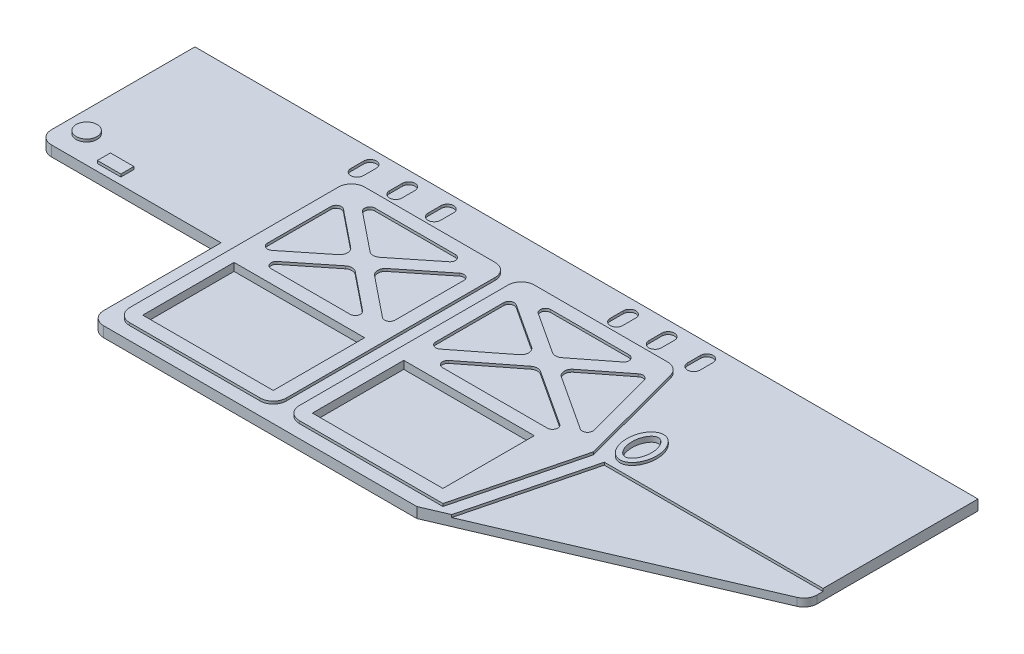
SolidWorks part; units mm, degrees
ref_plane "Front Plane" through (0, 0, 0) normal (0, 0, 1) x (1, 0, 0)
ref_plane "Top Plane" through (0, 0, 0) normal (0, 1, 0) x (1, 0, 0)
ref_plane "Right Plane" through (0, 0, 0) normal (1, 0, 0) x (0, 0, -1)
sketch "Sketch1" plane through (0, 0, 0) normal (0, 0, 1) x (1, 0, 0)
  line L0 (0, 0) -> (0, 254) construction
  line L1 (-381, 0) -> (0, 0)
  line L3 (-381, 6.35) -> (0, 6.35)
  line L4 (0, 0) -> (0, 6.35)
  line L5 (-381, 0) -> (-381, 6.35)
extrude "Boss-Extrude1" add sketch "Sketch1" along normal blind 139.7
sketch "Sketch2" plane through (0, 0, 0) normal (0, -1, 0) x (1, 0, 0)
  line L1 (-406.4, 139.7) -> (-406.4, 0) construction
  line L2 (-374.65, 76.2) -> (-292.1, 76.2)
  line L3 (-292.1, 76.2) -> (-292.1, 133.35)
  line L4 (-381, 139.7) -> (0, 139.7) construction
  line L5 (-285.75, 139.7) -> (-133.35, 139.7)
  line L6 (-133.35, 139.7) -> (-3.8486, 84.1994)
  line L7 (0, 139.7) -> (0, 0) construction
  line L8 (0, 78.3628) -> (0, 0)
  line L9 (0, 0) -> (-381, 0)
  line L10 (-381, 69.85) -> (-381, 0)
  line L11 (-381, 139.7) -> (-381, 0) construction
  arc A0 (-3.8486, 84.1994) -> (0, 78.3628) centre (-6.35, 78.3628) cw
  arc A1 (-292.1, 133.35) -> (-285.75, 139.7) centre (-285.75, 133.35) cw
  arc A3 (-381, 69.85) -> (-374.65, 76.2) centre (-374.65, 69.85) cw
  point P17 (0, 82.55)
  point P20 (-292.1, 139.7)
  point P21 (-381, 76.2)
  point P23 (-406.4, 76.2)
  dimension "D5" = 6.35
  dimension "D1" = 6.35
  dimension "D2" = 114.3
  dimension "D3" = 158.75
  dimension "D4" = 82.55
extrude "Cut-Extrude1" cut sketch "Sketch2" against normal through all
sketch "Sketch3" plane through (0, 6.35, 0) normal (0, 1, 0) x (1, 0, 0)
  line L0 (-133.35, -139.7) -> (-285.75, -139.7) construction
  line L1 (-279.4, -127) -> (-215.9, -127)
  line L2 (-279.4, -127) -> (-279.4, -82.55)
  line L3 (-279.4, -82.55) -> (-215.9, -82.55)
  line L4 (-215.9, -127) -> (-215.9, -82.55)
  line L5 (-196.85, -127) -> (-133.35, -127)
  line L6 (-196.85, -127) -> (-196.85, -82.55)
  line L7 (-196.85, -82.55) -> (-133.35, -82.55)
  line L8 (-133.35, -127) -> (-133.35, -82.55)
  line L9 (-292.1, -76.2) -> (-292.1, -133.35) construction
  dimension "D1" = 44.45
  dimension "D2" = 12.7
  dimension "D3" = 12.7
  dimension "D4" = 63.5
  dimension "D5" = 19.05
  dimension "D6" = 44.45
  dimension "D7" = 12.7
  dimension "D8" = 63.5
extrude "Cut-Extrude2" cut sketch "Sketch3" against normal through all contours L5 L8 L7 L6 | L1 L4 L3 L2
sketch "Sketch4" plane through (0, 0, 0) normal (0, -1, 0) x (1, 0, 0)
  line L0 (-285.75, 139.7) -> (-133.35, 139.7) construction
  line L1 (-279.4, 133.35) -> (-215.9, 133.35)
  line L2 (-285.75, 127) -> (-285.75, 25.4)
  line L3 (-279.4, 19.05) -> (-215.9, 19.05)
  line L4 (-209.55, 127) -> (-209.55, 25.4)
  line L5 (-127, 133.35) -> (-196.85, 133.35)
  line L7 (-131.8807, 19.05) -> (-196.85, 19.05)
  line L8 (-203.2, 127) -> (-203.2, 25.4)
  line L9 (-292.1, 76.2) -> (-292.1, 133.35) construction
  line L11 (-381, 0) -> (0, 0) construction
  line L12 (-215.9, 127) -> (-215.9, 82.55) construction
  line L13 (-127, 133.35) -> (-112.1376, 74.8789)
  line L14 (-112.1376, 74.8789) -> (-125.7444, 23.7664)
  arc A0 (-196.85, 133.35) -> (-203.2, 127) centre (-196.85, 127) ccw
  arc A1 (-215.9, 133.35) -> (-209.55, 127) centre (-215.9, 127) cw
  arc A2 (-279.4, 133.35) -> (-285.75, 127) centre (-279.4, 127) ccw
  arc A3 (-285.75, 25.4) -> (-279.4, 19.05) centre (-279.4, 25.4) ccw
  arc A4 (-215.9, 19.05) -> (-209.55, 25.4) centre (-215.9, 25.4) ccw
  arc A5 (-196.85, 19.05) -> (-203.2, 25.4) centre (-196.85, 25.4) cw
  arc A6 (-131.8807, 19.05) -> (-125.7444, 23.7664) centre (-131.8807, 25.4) ccw
  dimension "D3" = 6.35
  dimension "D1" = 6.35
  dimension "D2" = 6.35
  dimension "D4" = 6.35
  dimension "D5" = 19.05
  dimension "D6" = 6.35
  dimension "D7" = 6.35
  dimension "D8" = 19.05
extrude "Cut-Extrude3" cut sketch "Sketch4" against normal blind 1.27
sketch "Sketch5" plane through (0, 0, 0) normal (0, -1, 0) x (1, 0, 0)
  line L0 (-250.8616, 56.914) -> (-269.3149, 71.6766)
  line L1 (-248.4216, 50.9666) -> (-248.4331, 50.9773) construction
  line L3 (-267.7282, 76.2) -> (-229.317, 76.2)
  line L4 (-257.258, 53.8991) -> (-275.2733, 68.3113)
  line L5 (-184.3234, 76.2) -> (-133.6398, 76.2)
  line L6 (-196.85, 82.55) -> (-133.35, 82.55) construction
  line L9 (-142.8427, 29.9409) -> (-159.4602, 42.9343)
  line L10 (-227.2884, 29.9234) -> (-246.082, 44.9583)
  line L12 (-131.9836, 71.533) -> (-158.9921, 53.9033)
  line L15 (-124.9851, 68.5182) -> (-151.5288, 51.1918)
  line L21 (-220.0267, 32.246) -> (-239.6856, 47.9731)
  line L24 (-275.269, 33.4756) -> (-257.2515, 47.954)
  line L26 (-131.8807, 25.4) -> (-118.6989, 74.9159)
  line L28 (-131.8807, 25.4) -> (-118.6989, 74.9159)
  line L30 (-118.6989, 74.9159) -> (-131.9379, 127)
  line L37 (-269.5564, 29.9199) -> (-250.8486, 44.9531)
  line L38 (-215.9, 34.2294) -> (-215.9, 67.7374)
  line L40 (-248.5328, 50.9091) -> (-248.3486, 51.0351) construction
  line L41 (-246.095, 56.9191) -> (-227.7259, 71.6801)
  line L42 (-248.5328, 50.9091) -> (-248.5037, 50.8894) construction
  line L43 (-228.8751, 25.4) -> (-267.9653, 25.4)
  line L44 (-248.3486, 51.0351) -> (-248.5037, 50.8894) construction
  line L45 (-279.4, 66.3279) -> (-279.4, 35.4556)
  line L46 (-239.6921, 53.9182) -> (-220.031, 69.7173)
  line L47 (-133.6398, 76.2) -> (-133.372, 76.2)
  line L51 (-134.0223, 31.1049) -> (-151.793, 45)
  line L55 (-163.4215, 54.0923) -> (-185.888, 71.6591)
  line L57 (-164.1074, 50.5642) -> (-164.3654, 50.8) construction
  line L58 (-131.9379, 127) -> (-196.85, 127)
  line L59 (-171.3529, 45.8348) -> (-192.9216, 31.7558)
  line L60 (-164.3654, 50.8) -> (-164.0586, 50.5961) construction
  line L61 (-196.85, 127) -> (-196.85, 25.4)
  line L62 (-164.0586, 50.5961) -> (-164.1074, 50.5642)
  line L63 (-171.0886, 52.0266) -> (-192.7454, 68.9603)
  line L65 (-163.8896, 43.1233) -> (-183.8917, 30.067)
  line L66 (-196.85, 127) -> (-196.85, 25.4)
  line L68 (-196.85, 25.4) -> (-131.8807, 25.4)
  line L70 (-196.85, 25.4) -> (-131.8807, 25.4)
  arc A0 (-257.258, 53.8991) -> (-257.2515, 47.954) centre (-259.6381, 50.924) cw
  arc A1 (-250.8486, 44.9531) -> (-246.082, 44.9583) centre (-248.462, 41.9831) cw
  arc A2 (-239.6856, 47.9731) -> (-239.6921, 53.9182) centre (-237.3055, 50.9483) cw
  arc A3 (-250.8616, 56.914) -> (-246.095, 56.9191) centre (-248.4815, 59.8891) ccw
  arc A4 (-267.7282, 76.2) -> (-269.3149, 71.6766) centre (-267.7282, 73.66) ccw
  arc A5 (-275.2733, 68.3113) -> (-279.4, 66.3279) centre (-276.86, 66.3279) ccw
  arc A6 (-279.4, 35.4556) -> (-275.269, 33.4756) centre (-276.86, 35.4556) ccw
  arc A7 (-267.9653, 25.4) -> (-269.5564, 29.9199) centre (-267.9653, 27.94) cw
  arc A8 (-227.2884, 29.9234) -> (-228.8751, 25.4) centre (-228.8751, 27.94) cw
  arc A9 (-220.0267, 32.246) -> (-215.9, 34.2294) centre (-218.44, 34.2294) ccw
  arc A10 (-215.9, 67.7374) -> (-220.031, 69.7173) centre (-218.44, 67.7374) ccw
  arc A11 (-227.7259, 71.6801) -> (-229.317, 76.2) centre (-229.317, 73.66) ccw
  arc A12 (-183.8917, 30.067) -> (-182.5033, 25.4) centre (-182.5033, 27.94) ccw
  arc A13 (-142.8427, 29.9409) -> (-144.4073, 25.4) centre (-144.4073, 27.94) cw
  arc A14 (-124.9851, 68.5182) -> (-121.1422, 65.7378) centre (-123.5967, 66.3912) cw
  arc A15 (-133.372, 76.2) -> (-131.9836, 71.533) centre (-133.372, 73.66) cw
  arc A16 (-134.0223, 31.1049) -> (-130.0033, 32.4524) centre (-132.4578, 33.1058) ccw
  arc A17 (-192.9216, 31.7558) -> (-196.85, 33.8828) centre (-194.31, 33.8828) cw
  arc A18 (-196.85, 66.9593) -> (-192.7454, 68.9603) centre (-194.31, 66.9593) cw
  arc A19 (-185.888, 71.6591) -> (-184.3234, 76.2) centre (-184.3234, 73.66) cw
  arc A20 (-171.3529, 45.8348) -> (-171.0886, 52.0266) centre (-173.4355, 49.0252) ccw
  arc A21 (-163.8896, 43.1233) -> (-159.4602, 42.9343) centre (-161.807, 39.9329) cw
  arc A22 (-151.793, 45) -> (-151.5288, 51.1918) centre (-149.4462, 48.0014) cw
  arc A23 (-158.9921, 53.9033) -> (-163.4215, 54.0923) centre (-161.0746, 57.0937) cw
  point P13 (-247.9043, 50.4821)
  point P14 (-248.3486, 51.0351)
  point P39 (-243.3962, 50.9416)
  point P55 (-157.9377, 50.8)
  point P56 (-164.3654, 50.8)
  point P88 (-166.8929, 48.746)
  dimension "D5" = 3.81
  dimension "D1" = 2.54
  dimension "D4" = 2.54
  dimension "D6" = 2.54
  dimension "D7" = 2.54
  dimension "D8" = 3.81
  dimension "D3" = 6.35
  dimension "D2" = 6.35
extrude "Cut-Extrude4" cut sketch "Sketch5" against normal blind 1.27 contours A23 L12 A15 L47 L5 A19 L55 | A22 L51 A16 L28 A14 L15 | A21 L65 A12 L70 A13 L9 | L59 A20 L63 A18 L66 A17 | L38 A10 L46 A2 L21 A9 | A8 L10 A1 L37 A7 L43 | L41 A11 L3 A4 L0 A3 | L45 A6 L24 A0 L4 A5
sketch "Sketch6" plane through (0, 1.27, 0) normal (0, -1, 0) x (1, 0, 0)
  line L0 (-288.798, 6.985) -> (-288.798, 13.335) construction
  line L1 (-291.846, 6.985) -> (-291.846, 13.335)
  line L2 (-285.75, 6.985) -> (-285.75, 13.335)
  line L3 (-270.002, 6.985) -> (-270.002, 13.335) construction
  line L6 (-273.05, 6.985) -> (-273.05, 13.335)
  line L9 (-266.954, 6.985) -> (-266.954, 13.335)
  line L12 (-251.206, 6.985) -> (-251.206, 13.335) construction
  line L15 (-381, 0) -> (0, 0) construction
  line L17 (-254.254, 6.985) -> (-254.254, 13.335)
  line L18 (-248.158, 6.985) -> (-248.158, 13.335)
  line L19 (-162.56, 6.985) -> (-162.56, 13.335) construction
  line L20 (-165.608, 6.985) -> (-165.608, 13.335)
  line L21 (-159.512, 6.985) -> (-159.512, 13.335)
  line L22 (-143.764, 6.985) -> (-143.764, 13.335) construction
  line L23 (-146.812, 6.985) -> (-146.812, 13.335)
  line L24 (-140.716, 6.985) -> (-140.716, 13.335)
  line L25 (-124.968, 6.985) -> (-124.968, 13.335) construction
  line L26 (-128.016, 6.985) -> (-128.016, 13.335)
  line L27 (-121.92, 6.985) -> (-121.92, 13.335)
  line L28 (-381, 69.85) -> (-381, 0) construction
  arc A0 (-291.846, 6.985) -> (-285.75, 6.985) centre (-288.798, 6.985) ccw
  arc A1 (-285.75, 13.335) -> (-291.846, 13.335) centre (-288.798, 13.335) ccw
  arc A5 (-286.5205, 4.8853) -> (-286.5215, 4.9583) centre (-289.4119, 4.8853) ccw
  arc A7 (-286.5205, 4.8853) -> (-286.5215, 4.9583) centre (-289.4119, 4.8853) ccw
  arc A9 (-286.5205, 4.8853) -> (-286.5215, 4.9583) centre (-289.4119, 4.8853) ccw
  arc A10 (-273.05, 6.985) -> (-266.954, 6.985) centre (-270.002, 6.985) ccw
  arc A11 (-266.954, 13.335) -> (-273.05, 13.335) centre (-270.002, 13.335) ccw
  arc A12 (-254.254, 6.985) -> (-248.158, 6.985) centre (-251.206, 6.985) ccw
  arc A13 (-248.158, 13.335) -> (-254.254, 13.335) centre (-251.206, 13.335) ccw
  arc A14 (-165.608, 6.985) -> (-159.512, 6.985) centre (-162.56, 6.985) ccw
  arc A15 (-159.512, 13.335) -> (-165.608, 13.335) centre (-162.56, 13.335) ccw
  arc A16 (-146.812, 6.985) -> (-140.716, 6.985) centre (-143.764, 6.985) ccw
  arc A17 (-140.716, 13.335) -> (-146.812, 13.335) centre (-143.764, 13.335) ccw
  arc A18 (-128.016, 6.985) -> (-121.92, 6.985) centre (-124.968, 6.985) ccw
  arc A19 (-121.92, 13.335) -> (-128.016, 13.335) centre (-124.968, 13.335) ccw
  point P2 (-288.798, 10.16)
  point P9 (-289.4119, -1.7103)
  point P11 (-270.002, 10.16)
  point P16 (-289.4119, 0)
  point P18 (-251.206, 10.16)
  point P23 (-289.4119, 0)
  point P28 (-162.56, 10.16)
  point P30 (-289.4119, 0)
  point P41 (-143.764, 10.16)
  point P48 (-124.968, 10.16)
  point P57 (-248.158, 10.16)
  dimension "D1" = 3.048
  dimension "D2" = 6.35
  dimension "D3" = 10.16
  dimension "D4" = 95.25
  dimension "D5" = 12.7
  dimension "D6" = 12.7
  dimension "D7" = 82.55
  dimension "D8" = 12.7
  dimension "D9" = 12.7
extrude "Cut-Extrude5" cut sketch "Sketch6" against normal blind 1.27 contours L18 A13 L17 A12 | L21 A15 L20 A14 | L24 A17 L23 A16 | L27 A19 L26 A18 | L9 A11 L6 A10 | L2 A1 L1 A0
sketch "Sketch7" plane through (0, 1.27, 0) normal (0, -1, 0) x (1, 0, 0)
  ellipse E0 centre (-102.3292, 61.2539) end of major axis (-102.3292, 71.8921) minor radius 7.2651
extrude "Boss-Extrude2" add sketch "Sketch7" along normal blind 1.27
sketch "Sketch8" plane through (0, 0, 0) normal (0, -1, 0) x (1, 0, 0)
  spline S0 degree 3 poles (-102.5457, 53.1558) (-102.1128, 53.1558) (-101.9017, 53.1847) (-101.4887, 53.2926) (-101.286, 53.3725) (-100.9061, 53.5658) (-100.7263, 53.6798) (-100.3826, 53.9355) (-100.2199, 54.0767) (-99.7641, 54.523) (-99.4978, 54.8539) (-99.0202, 55.5645) (-98.8146, 55.9368) (-98.4565, 56.7025) (-98.3038, 57.0969) (-98.0439, 57.9056) (-97.9369, 58.3207) (-97.6852, 59.5649) (-97.6045, 60.4029) (-97.604, 61.6715) (-97.6245, 62.0987) (-97.7076, 62.9434) (-97.7697, 63.3607) (-98.0198, 64.5967) (-98.2685, 65.4004) (-98.8106, 66.5641) (-99.0169, 66.9375) (-99.4909, 67.6447) (-99.7614, 67.9817) (-100.2165, 68.4281) (-100.3767, 68.5675) (-100.7186, 68.8228) (-100.9015, 68.9393) (-101.2816, 69.1335) (-101.4804, 69.2125) (-101.8977, 69.3226) (-102.1082, 69.3513) (-102.5329, 69.3528) (-102.7497, 69.3244) (-103.1637, 69.2174) (-103.3649, 69.1387) (-103.748, 68.9447) (-103.9279, 68.8308) (-104.2697, 68.5773) (-104.4325, 68.4367) (-104.8923, 67.9876) (-105.1581, 67.6571) (-105.6325, 66.9527) (-105.8414, 66.5759) (-106.381, 65.423) (-106.6338, 64.6169) (-106.8884, 63.364) (-106.9508, 62.9429) (-107.0335, 62.1027) (-107.0541, 61.6823) (-107.0545, 60.8405) (-107.0345, 60.4193) (-106.9523, 59.576) (-106.8897, 59.1521) (-106.6374, 57.9049) (-106.3864, 57.0988) (-105.8458, 55.9402) (-105.6383, 55.5651) (-105.2832, 55.0361) (-105.1572, 54.8648) (-104.8873, 54.5343) (-104.7428, 54.3746) (-104.4383, 54.0765) (-104.2778, 53.9373) (-103.9365, 53.6828) (-103.7539, 53.5667) (-103.3731, 53.3727) (-103.175, 53.2943) (-102.7592, 53.185) (-102.5457, 53.1558) (-102.1128, 53.1558) (-101.9017, 53.1847) knots -0.015625 -0.015625 0 0 0.015625 0.015625 0.03125 0.03125 0.046875 0.046875 0.0625 0.0625 0.09375 0.09375 0.125 0.125 0.15625 0.15625 0.1875 0.1875 0.25 0.25 0.28125 0.28125 0.3125 0.3125 0.375 0.375 0.40625 0.40625 0.4375 0.4375 0.453125 0.453125 0.46875 0.46875 0.484375 0.484375 0.5 0.5 0.515625 0.515625 0.53125 0.53125 0.546875 0.546875 0.5625 0.5625 0.59375 0.59375 0.625 0.625 0.6875 0.6875 0.71875 0.71875 0.75 0.75 0.78125 0.78125 0.8125 0.8125 0.875 0.875 0.90625 0.90625 0.921875 0.921875 0.9375 0.9375 0.953125 0.953125 0.96875 0.96875 0.984375 0.984375 1 1 1.015625 1.015625 1.03125 only from (-102.3292, 53.1558) to (-102.3292, 53.1558)
  spline S1 degree 3 poles (-102.5457, 53.1558) (-102.1128, 53.1558) (-101.9017, 53.1847) (-101.4887, 53.2926) (-101.286, 53.3725) (-100.9061, 53.5658) (-100.7263, 53.6798) (-100.3826, 53.9355) (-100.2199, 54.0767) (-99.7641, 54.523) (-99.4978, 54.8539) (-99.0202, 55.5645) (-98.8146, 55.9368) (-98.4565, 56.7025) (-98.3038, 57.0969) (-98.0439, 57.9056) (-97.9369, 58.3207) (-97.6852, 59.5649) (-97.6045, 60.4029) (-97.604, 61.6715) (-97.6245, 62.0987) (-97.7076, 62.9434) (-97.7697, 63.3607) (-98.0198, 64.5967) (-98.2685, 65.4004) (-98.8106, 66.5641) (-99.0169, 66.9375) (-99.4909, 67.6447) (-99.7614, 67.9817) (-100.2165, 68.4281) (-100.3767, 68.5675) (-100.7186, 68.8228) (-100.9015, 68.9393) (-101.2816, 69.1335) (-101.4804, 69.2125) (-101.8977, 69.3226) (-102.1082, 69.3513) (-102.5329, 69.3528) (-102.7497, 69.3244) (-103.1637, 69.2174) (-103.3649, 69.1387) (-103.748, 68.9447) (-103.9279, 68.8308) (-104.2697, 68.5773) (-104.4325, 68.4367) (-104.8923, 67.9876) (-105.1581, 67.6571) (-105.6325, 66.9527) (-105.8414, 66.5759) (-106.381, 65.423) (-106.6338, 64.6169) (-106.8884, 63.364) (-106.9508, 62.9429) (-107.0335, 62.1027) (-107.0541, 61.6823) (-107.0545, 60.8405) (-107.0345, 60.4193) (-106.9523, 59.576) (-106.8897, 59.1521) (-106.6374, 57.9049) (-106.3864, 57.0988) (-105.8458, 55.9402) (-105.6383, 55.5651) (-105.2832, 55.0361) (-105.1572, 54.8648) (-104.8873, 54.5343) (-104.7428, 54.3746) (-104.4383, 54.0765) (-104.2778, 53.9373) (-103.9365, 53.6828) (-103.7539, 53.5667) (-103.3731, 53.3727) (-103.175, 53.2943) (-102.7592, 53.185) (-102.5457, 53.1558) (-102.1128, 53.1558) (-101.9017, 53.1847) knots -0.015625 -0.015625 0 0 0.015625 0.015625 0.03125 0.03125 0.046875 0.046875 0.0625 0.0625 0.09375 0.09375 0.125 0.125 0.15625 0.15625 0.1875 0.1875 0.25 0.25 0.28125 0.28125 0.3125 0.3125 0.375 0.375 0.40625 0.40625 0.4375 0.4375 0.453125 0.453125 0.46875 0.46875 0.484375 0.484375 0.5 0.5 0.515625 0.515625 0.53125 0.53125 0.546875 0.546875 0.5625 0.5625 0.59375 0.59375 0.625 0.625 0.6875 0.6875 0.71875 0.71875 0.75 0.75 0.78125 0.78125 0.8125 0.8125 0.875 0.875 0.90625 0.90625 0.921875 0.921875 0.9375 0.9375 0.953125 0.953125 0.96875 0.96875 0.984375 0.984375 1 1 1.015625 1.015625 1.03125 only from (-102.3292, 53.1558) to (-102.3292, 53.1558)
  dimension "D1" = 2.54
extrude "Cut-Extrude6" cut sketch "Sketch8" against normal blind 2.54
sketch "Sketch9" plane through (0, 1.27, 0) normal (0, -1, 0) x (1, 0, 0)
  circle A0 centre (-20.3877, 60.8315) radius 7.62
  dimension "D1" = 15.24
extrude "Boss-Extrude3" add sketch "Sketch9" along normal blind 1.27
sketch "Sketch10" plane through (0, 0, 0) normal (0, -1, 0) x (1, 0, 0)
  circle A2 centre (-20.3877, 60.8315) radius 5.08
  circle A3 centre (-20.3877, 60.8315) radius 5.08
  dimension "D1" = 2.54
extrude "Cut-Extrude7" cut sketch "Sketch10" against normal blind 2.54
sketch "Sketch13" plane through (0, 1.27, 0) normal (0, -1, 0) x (1, 0, 0)
  line L0 (-119.1478, 125.4549) -> (-106.4217, 75.3886)
  line L1 (-106.4217, 75.3886) -> (0, 75.3886)
  line L2 (0, 0) -> (0, 78.3628) construction
  line L3 (-119.1478, 125.4549) -> (-121.475, 134.6107)
  line L4 (-3.8486, 84.1994) -> (-133.35, 139.7) construction
  line L5 (0, 75.3886) -> (0, 78.3628)
  line L6 (-3.8486, 84.1994) -> (-121.475, 134.6107)
  arc A0 (0, 78.3628) -> (-3.8486, 84.1994) centre (-6.35, 78.3628) ccw construction
  arc A1 (0, 78.3628) -> (-3.8486, 84.1994) centre (-6.35, 78.3628) ccw
extrude "Cut-Extrude10" cut sketch "Sketch13" against normal blind 1.27 contours L5 A1 L6 L3 L0 L1
sketch "Sketch14" plane through (0, 1.27, 0) normal (0, -1, 0) x (1, 0, 0)
  line L1 (-355.6, 72.8674) -> (-344.17, 72.8674)
  line L2 (-355.6, 72.8674) -> (-355.6, 66.5174)
  line L3 (-355.6, 66.5174) -> (-344.17, 66.5174)
  line L4 (-344.17, 72.8674) -> (-344.17, 66.5174)
  line L6 (-381, 69.85) -> (-381, 0) construction
  circle A0 centre (-370.84, 62.8553) radius 5.08
  dimension "D1" = 10.16
  dimension "D5" = 10.16
  dimension "D2" = 25.4
  dimension "D3" = 6.35
  dimension "D4" = 11.43
extrude "Boss-Extrude4" add sketch "Sketch14" along normal blind 1.27
ref_plane "Plane2" through (0, 3.175, 0) normal (0, -1, 0) x (-1, 0, 0)
mirror "Mirror7" about plane through (0, 3.175, 0) normal (0, -1, 0) of "Cut-Extrude3"
mirror "Mirror8" about plane through (0, 3.175, 0) normal (0, -1, 0) of "Cut-Extrude6", "Boss-Extrude2", "Cut-Extrude5", "Cut-Extrude4"
mirror "Mirror9" about plane through (0, 3.175, 0) normal (0, -1, 0) of "Boss-Extrude4", "Cut-Extrude10"
sketch "Sketch15" plane through (0, 1.27, 0) normal (0, -1, 0) x (1, 0, 0)
  line L0 (-381, 69.85) -> (-381, 0) construction
  line L1 (-292.1, 76.2) -> (-374.65, 76.2) construction
  line L2 (-292.1, 133.35) -> (-292.1, 76.2) construction
  line L3 (-133.35, 139.7) -> (-285.75, 139.7) construction
  line L4 (-121.475, 134.6107) -> (-133.35, 139.7) construction
  line L5 (-3.8486, 84.1994) -> (-121.475, 134.6107) construction
  line L6 (0, 75.3886) -> (0, 78.3628) construction
  line L7 (0, 0) -> (0, 75.3886) construction
  line L8 (-381, 0) -> (0, 0) construction
  line L9 (-381, 69.85) -> (-381, 0)
  line L10 (-292.1, 76.2) -> (-374.65, 76.2)
  line L12 (-292.1, 133.35) -> (-292.1, 76.2)
  line L13 (-133.35, 139.7) -> (-285.75, 139.7)
  line L14 (-121.475, 134.6107) -> (-133.35, 139.7)
  line L15 (-3.8486, 84.1994) -> (-121.475, 134.6107)
  line L16 (0, 75.3886) -> (0, 78.3628)
  line L27 (0, 0) -> (0, 75.3886)
  line L28 (-381, 0) -> (0, 0)
  arc A0 (-374.65, 76.2) -> (-381, 69.85) centre (-374.65, 69.85) ccw construction
  arc A1 (-285.75, 139.7) -> (-292.1, 133.35) centre (-285.75, 133.35) ccw construction
  arc A2 (0, 78.3628) -> (-3.8486, 84.1994) centre (-6.35, 78.3628) ccw construction
  arc A3 (-374.65, 76.2) -> (-381, 69.85) centre (-374.65, 69.85) ccw
  arc A6 (-285.75, 139.7) -> (-292.1, 133.35) centre (-285.75, 133.35) ccw
  arc A7 (0, 78.3628) -> (-3.8486, 84.1994) centre (-6.35, 78.3628) ccw
extrude "Boss-Extrude5" add sketch "Sketch15" along normal blind 1.27 and the other way blind 1.27
